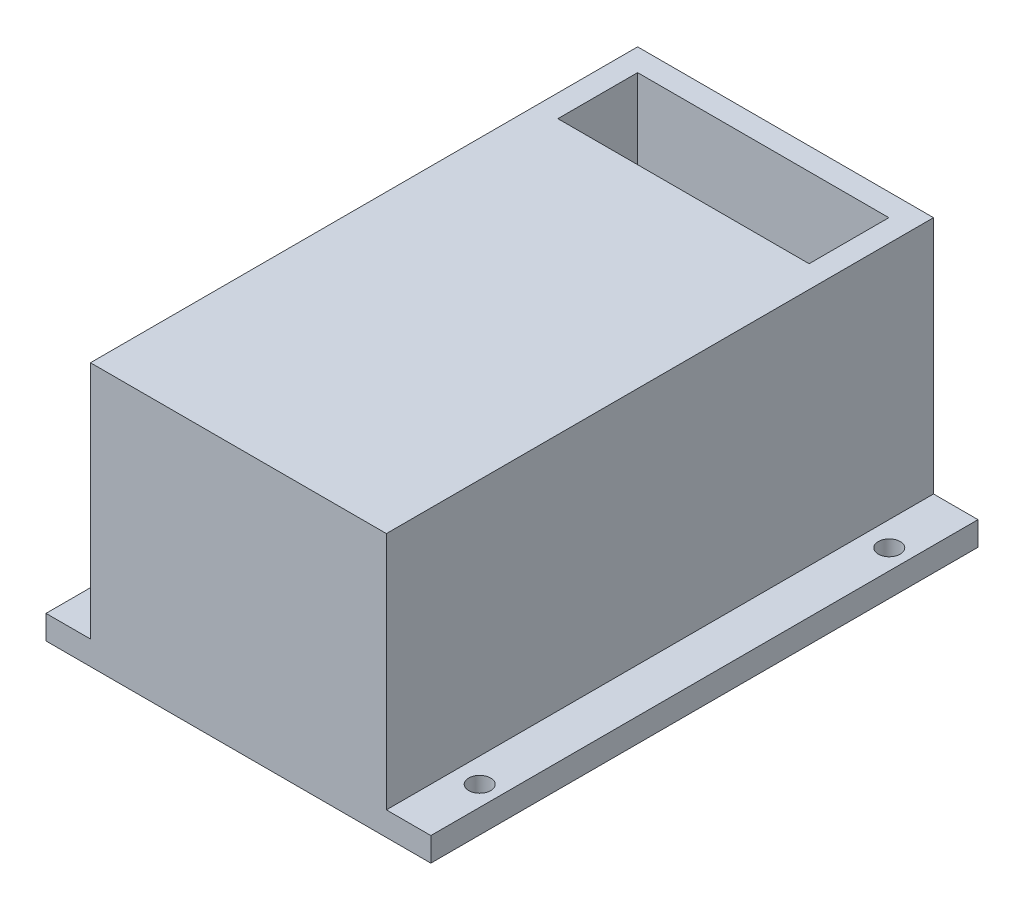
SolidWorks part; units mm, degrees
ref_plane "Front Plane" through (0, 0, 0) normal (0, 0, 1) x (1, 0, 0)
ref_plane "Top Plane" through (0, 0, 0) normal (0, 1, 0) x (1, 0, 0)
ref_plane "Right Plane" through (0, 0, 0) normal (1, 0, 0) x (0, 0, -1)
sketch "Sketch1" plane through (0, 0, 0) normal (0, 1, 0) x (1, 0, 0)
  line L1 (0, 0) -> (31.5, 0)
  line L2 (0, 0) -> (0, 63)
  line L3 (0, 63) -> (31.5, 63)
  line L4 (31.5, 0) -> (31.5, 63)
  dimension "D1" = 63
  dimension "D2" = 31.5
sketch "Sketch2" plane through (0, 0, 0) normal (0, 1, 0) x (1, 0, 0)
  line L8 (-2.8, 65.8) -> (-2.8, -2.8)
  line L9 (-2.8, -2.8) -> (34.3, -2.8)
  line L10 (34.3, -2.8) -> (34.3, 65.8)
  line L11 (34.3, 65.8) -> (-2.8, 65.8)
  line L12 (-2.8, 65.8) -> (-2.8, -2.8)
  line L13 (-2.8, -2.8) -> (34.3, -2.8)
  line L14 (34.3, -2.8) -> (34.3, 65.8)
  line L15 (34.3, 65.8) -> (-2.8, 65.8)
  dimension "D1" = 2.8
extrude "Boss-Extrude1" add sketch "Sketch2" along normal blind 33
extrude "Cut-Extrude1" cut sketch "Sketch1" along normal offset from surface (30 mm away) 3 up to face at (15.75, 33, -31.5)
sketch "Sketch3" plane through (0, 30, 0) normal (0, -1, 0) x (1, 0, 0)
  line L0 (31.5, 0) -> (31.5, -63) construction
  line L1 (0, -63) -> (31.5, -63)
  line L2 (0, -63) -> (0, -53)
  line L3 (0, -53) -> (31.5, -53)
  line L4 (31.5, -63) -> (31.5, -53)
  dimension "D1" = 10
extrude "Cut-Extrude2" cut sketch "Sketch3" against normal blind 5
sketch "Sketch5" plane through (0, 0, 0) normal (0, -1, 0) x (1, 0, 0)
  line L0 (15.75, 2.8) -> (15.75, -65.8) construction
  line L1 (-2.8, 2.8) -> (34.3, 2.8) construction
  line L2 (34.3, -65.8) -> (-2.8, -65.8) construction
  line L4 (39.875, -2.075) -> (-8.375, -2.075) construction
  line L5 (39.875, -2.075) -> (39.875, -60.925) construction
  line L6 (39.875, -60.925) -> (-8.375, -60.925) construction
  line L7 (-8.375, -2.075) -> (-8.375, -60.925) construction
  line L8 (39.875, -2.075) -> (-8.375, -60.925) construction
  line L9 (39.875, -60.925) -> (-8.375, -2.075) construction
  point P6 (15.75, -31.5)
  point P7 (15.75, -31.5)
  dimension "D1" = 48.25
  dimension "D2" = 58.85
sketch "Sketch6" plane through (0, 0, 0) normal (0, -1, 0) x (1, 0, 0)
  line L0 (-2.8, 2.8) -> (34.3, 2.8) construction
  line L1 (34.3, -65.8) -> (39.875, -65.8)
  line L2 (34.3, -65.8) -> (34.3, 2.8)
  line L3 (34.3, 2.8) -> (39.875, 2.8)
  line L4 (39.875, -65.8) -> (39.875, 2.8)
  line L5 (39.875, -2.075) -> (39.875, -60.925) construction
  line L6 (15.75, 2.8) -> (15.75, -65.8) construction
  line L7 (39.875, -31.5) -> (-8.375, -31.5) construction
  line L8 (-8.375, -2.075) -> (-8.375, -60.925) construction
  line L9 (39.875, -60.925) -> (-8.375, -60.925) construction
  line L10 (-2.8, 2.8) -> (-8.375, 2.8)
  line L11 (-8.375, -65.8) -> (-8.375, 2.8)
  line L12 (-2.8, -65.8) -> (-8.375, -65.8)
  line L13 (-2.8, -65.8) -> (-2.8, 2.8)
  circle A0 centre (37.375, -57.175) radius 1.375
  circle A1 centre (37.375, -5.825) radius 1.375
  circle A2 centre (-5.875, -5.825) radius 1.375
  circle A3 centre (-5.875, -57.175) radius 1.375
  dimension "D1" = 2.75
  dimension "D2" = 3.75
  dimension "D3" = 2.5
extrude "Boss-Extrude2" add sketch "Sketch6" against normal blind 3
